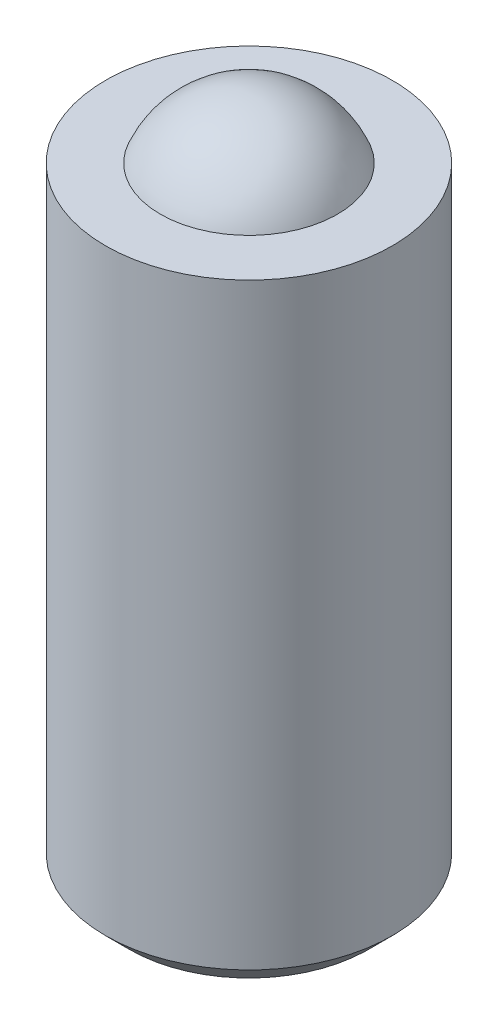
SolidWorks part; units mm, degrees
ref_plane "前视基准面" through (0, 0, 0) normal (0, 0, 1) x (1, 0, 0)
ref_plane "上视基准面" through (0, 0, 0) normal (0, 1, 0) x (1, 0, 0)
ref_plane "右视基准面" through (0, 0, 0) normal (1, 0, 0) x (0, 0, -1)
sketch "草图1" plane through (0, 0, 0) normal (1, 0, 0) x (0, 0, -1)
  line L0 (0, 46.2984) -> (0, -39.6162) construction
  line L1 (-16.4783, 0) -> (19.9104, 0) construction
  line L2 (-3.7081, 0) -> (-6, 0)
  line L3 (-6, 0) -> (-6, -25)
  line L4 (-6, -25) -> (-5, -26)
  line L5 (-5, -26) -> (0, -26)
  line L6 (0, 2.5) -> (0, -26)
  arc A0 (0, 2.5) -> (-3.7081, 0) centre (0, -1.5) ccw
  dimension "D1" = 4
  dimension "D4" = 26
  dimension "D2" = 6
  dimension "D3" = 1
  dimension "D5" = 1.5
  dimension "D6" = 1
revolve "旋转1" add sketch "草图1" angle 360 about L0
